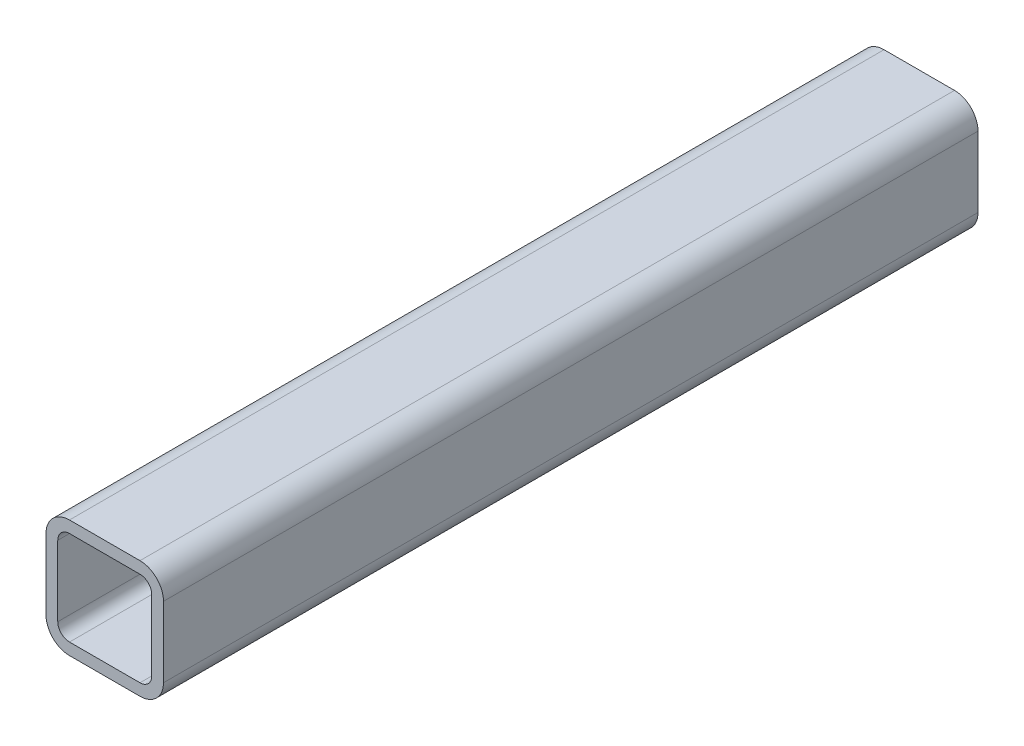
SolidWorks part; units mm, degrees
material "AISI 304"
ref_plane "Спереди" through (0, 0, 0) normal (0, 0, 1) x (1, 0, 0)
ref_plane "Сверху" through (0, 0, 0) normal (0, 1, 0) x (1, 0, 0)
ref_plane "Справа" through (0, 0, 0) normal (1, 0, 0) x (0, 0, -1)
sketch "Эскиз1" plane through (0, 0, 0) normal (0, 0, -1) x (-1, 0, 0)
  line L6 (-9, 12) -> (9, 12)
  line L7 (-9, -15) -> (9, -15)
  line L8 (-15, -9) -> (-15, 9)
  line L9 (-9, 15) -> (9, 15)
  line L10 (15, -9) -> (15, 9)
  line L11 (-15, -15) -> (15, 15) construction
  line L12 (-15, 15) -> (15, -15) construction
  line L13 (12, -9) -> (12, 9)
  line L14 (-9, -12) -> (9, -12)
  line L15 (-12, -9) -> (-12, 9)
  arc A3 (9, 15) -> (15, 9) centre (9, 9) cw
  arc A4 (9, -15) -> (15, -9) centre (9, -9) ccw
  arc A5 (-9, -15) -> (-15, -9) centre (-9, -9) cw
  arc A6 (-15, 9) -> (-9, 15) centre (-9, 9) cw
  arc A7 (9, 12) -> (12, 9) centre (9, 9) cw
  arc A8 (9, -12) -> (12, -9) centre (9, -9) ccw
  arc A9 (-9, -12) -> (-12, -9) centre (-9, -9) cw
  arc A10 (-12, 9) -> (-9, 12) centre (-9, 9) cw
  point P0 (0, 0)
  dimension "D3" = 6
  dimension "D1" = 30
  dimension "D2" = 30
  dimension "D4" = 3
extrude "Бобышка-Вытянуть1" add sketch "Эскиз1" along normal mid plane 208
